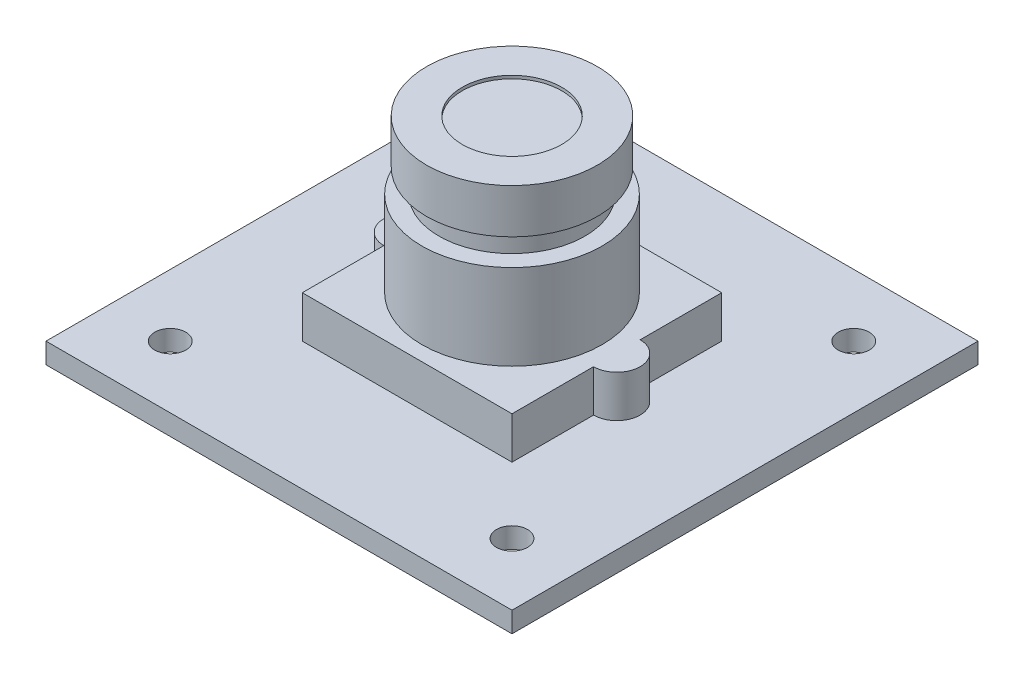
SolidWorks part; units mm, degrees
material "Rubber"
ref_plane "Front" through (0, 0, 0) normal (0, 0, 1) x (1, 0, 0)
ref_plane "Top" through (0, 0, 0) normal (0, 1, 0) x (1, 0, 0)
ref_plane "Right" through (0, 0, 0) normal (1, 0, 0) x (0, 0, -1)
sketch "Sketch1" plane through (0, 0, 0) normal (0, 1, 0) x (1, 0, 0)
  line L1 (-19.05, -19.05) -> (19.05, -19.05)
  line L2 (-19.05, -19.05) -> (-19.05, 19.05)
  line L3 (-19.05, 19.05) -> (19.05, 19.05)
  line L4 (19.05, -19.05) -> (19.05, 19.05)
  line L5 (-19.05, -19.05) -> (19.05, 19.05) construction
  line L6 (-19.05, 19.05) -> (19.05, -19.05) construction
  line L7 (-13.97, 13.97) -> (13.97, 13.97) construction
  line L8 (-13.97, 13.97) -> (-13.97, -13.97) construction
  line L9 (-13.97, -13.97) -> (13.97, -13.97) construction
  line L10 (13.97, 13.97) -> (13.97, -13.97) construction
  line L11 (-13.97, 13.97) -> (13.97, -13.97) construction
  line L12 (-13.97, -13.97) -> (13.97, 13.97) construction
  circle A0 centre (-13.97, 13.97) radius 1.27
  circle A1 centre (-13.97, -13.97) radius 1.27
  circle A2 centre (13.97, -13.97) radius 1.27
  circle A3 centre (13.97, 13.97) radius 1.27
  point P0 (0, 0)
  point P6 (0, 0)
  dimension "D5" = 2.54
  dimension "D1" = 38.1
  dimension "D2" = 38.1
  dimension "D3" = 27.94
  dimension "D4" = 27.94
extrude "Boss-Extrude1" add sketch "Sketch1" along normal blind 1.6764
sketch "Sketch2" plane through (0, 1.6764, 0) normal (0, 1, 0) x (1, 0, 0)
  line L0 (-8.5725, -1.905) -> (-8.5725, -8.5725)
  line L1 (-8.5725, 8.5725) -> (8.5725, 8.5725)
  line L2 (-8.5725, 8.5725) -> (-8.5725, 1.905)
  line L3 (-8.5725, -8.5725) -> (8.5725, -8.5725)
  line L4 (8.5725, 8.5725) -> (8.5725, 1.905)
  line L5 (-8.5725, 8.5725) -> (8.5725, -8.5725) construction
  line L6 (-8.5725, -8.5725) -> (8.5725, 8.5725) construction
  line L7 (8.5725, -1.905) -> (8.5725, -8.5725)
  line L8 (-8.5725, 1.905) -> (8.5725, 1.905) construction
  line L9 (8.5725, -1.905) -> (-8.5725, -1.905) construction
  line L10 (-10.4775, 0) -> (0, 0) construction
  arc A0 (-8.5725, 1.905) -> (-8.5725, -1.905) centre (-8.5725, 0) ccw
  arc A1 (8.5725, -1.905) -> (8.5725, 1.905) centre (8.5725, 0) ccw
  point P0 (0, 0)
  dimension "D3" = 3.81
  dimension "D1" = 17.145
  dimension "D2" = 17.145
extrude "Boss-Extrude2" add sketch "Sketch2" along normal blind 3.429
sketch "Sketch3" plane through (0, 5.1054, 0) normal (0, 1, 0) x (1, 0, 0)
  circle A0 centre (0, 0) radius 7.366
  dimension "D1" = 14.732
extrude "Boss-Extrude3" add sketch "Sketch3" along normal blind 6.985
sketch "Sketch4" plane through (0, 12.0904, 0) normal (0, 1, 0) x (1, 0, 0)
  circle A0 centre (0, 0) radius 5.969
  dimension "D1" = 11.938
extrude "Boss-Extrude4" add sketch "Sketch4" along normal blind 1.905
sketch "Sketch5" plane through (0, 13.9954, 0) normal (0, 1, 0) x (1, 0, 0)
  circle A0 centre (0, 0) radius 6.985
  dimension "D1" = 13.97
extrude "Boss-Extrude5" add sketch "Sketch5" along normal blind 3.6322
sketch "Sketch6" plane through (0, 17.6276, 0) normal (0, 1, 0) x (1, 0, 0)
  circle A0 centre (0, 0) radius 4.064
  dimension "D1" = 8.128
extrude "Cut-Extrude1" cut sketch "Sketch6" against normal blind 0.254
sketch "Sketch7" plane through (0, 0, 0) normal (0, -1, 0) x (1, 0, 0)
  line L0 (19.05, -19.05) -> (-19.05, -19.05) construction
  line L1 (-0.889, -11.0236) -> (-10.922, -11.0236)
  line L2 (-0.889, -11.0236) -> (-0.889, -15.748)
  line L3 (-0.889, -15.748) -> (-10.922, -15.748)
  line L4 (-10.922, -11.0236) -> (-10.922, -15.748)
  line L5 (-19.05, -19.05) -> (-19.05, 19.05) construction
  line L6 (-1.524, -11.6586) -> (-1.524, -15.113)
  line L7 (-1.524, -15.113) -> (-10.287, -15.113)
  line L8 (-10.287, -11.6586) -> (-10.287, -15.113)
  line L9 (-1.524, -11.6586) -> (-10.287, -11.6586)
  dimension "D1" = 3.302
  dimension "D2" = 4.7244
  dimension "D3" = 10.033
  dimension "D4" = 8.128
  dimension "D5" = 0.635
extrude "Boss-Extrude6" add sketch "Sketch7" along normal blind 6.604
sketch "Sketch9" plane through (0, 0, -11.0236) normal (0, 0, 1) x (1, 0, 0)
  line L0 (-5.9055, -6.604) -> (-5.9055, 0) construction
  line L1 (-0.889, -6.604) -> (-10.922, -6.604) construction
  line L2 (-0.889, 0) -> (-10.922, 0) construction
  line L4 (-4.318, 0) -> (-7.493, 0)
  line L5 (-4.318, 0) -> (-4.318, -6.604)
  line L6 (-4.318, -6.604) -> (-7.493, -6.604)
  line L7 (-7.493, 0) -> (-7.493, -6.604)
  line L8 (-4.318, 0) -> (-7.493, -6.604) construction
  line L9 (-4.318, -6.604) -> (-7.493, 0) construction
  point P6 (-5.9055, -3.302)
  dimension "D1" = 3.175
extrude "Cut-Extrude2" cut sketch "Sketch9" against normal up to next
